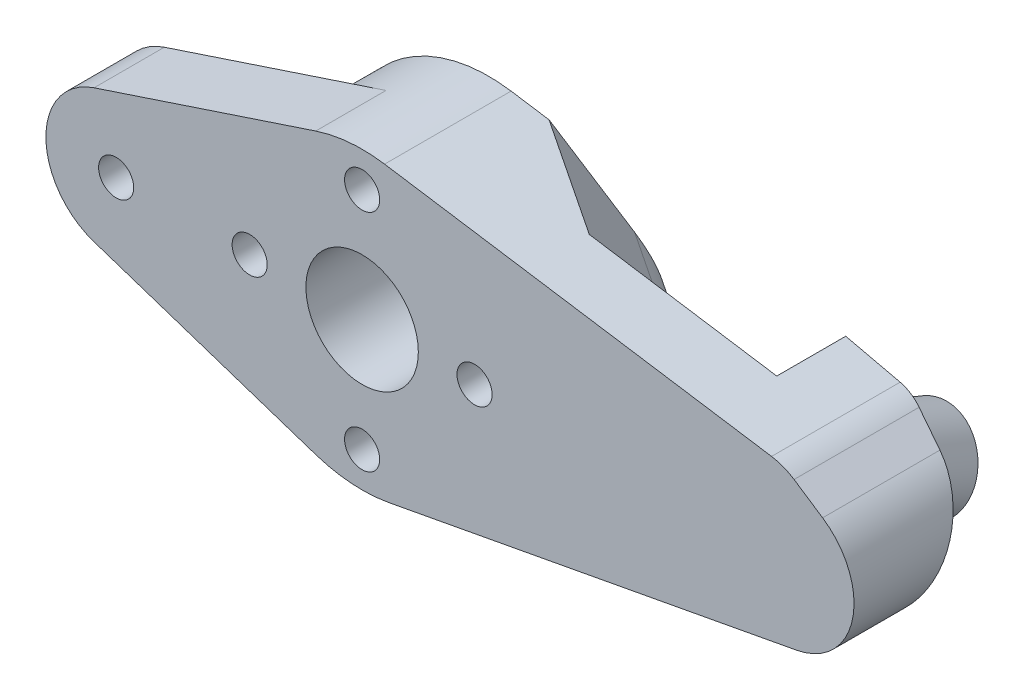
SolidWorks part; units mm, degrees
ref_plane "Plan de face" through (0, 0, 0) normal (0, 0, 1) x (1, 0, 0)
ref_plane "Plan de dessus" through (0, 0, 0) normal (0, 1, 0) x (1, 0, 0)
ref_plane "Plan de droite" through (0, 0, 0) normal (1, 0, 0) x (0, 0, -1)
sketch "Esquisse1" plane through (0, 0, 0) normal (0, 0, 1) x (1, 0, 0)
  line L1 (30.9167, -4.9153) -> (1.925, -10.322)
  line L2 (1.5995, 10.3775) -> (30, 6)
  line L3 (30, 6) -> (32.7639, 4.1667)
  arc A0 (1.5995, 10.3775) -> (1.925, -10.322) centre (0, 0) ccw
  arc A1 (32.7639, 4.1667) -> (30.9167, -4.9153) centre (30, 0) cw
  dimension "D1" = 10.5
  dimension "D2" = 5
  dimension "D3" = 30
  dimension "D4" = 6
extrude "Boss.-Extru.1" add sketch "Esquisse1" along normal blind 10
sketch "Esquisse2" plane through (0, 0, 10) normal (0, 0, 1) x (1, 0, 0)
  circle A0 centre (0, 0) radius 4
  circle A1 centre (0, 8) radius 1.25
  circle A2 centre (8, 0) radius 1.25
  circle A3 centre (0, -8) radius 1.25
  circle A4 centre (-8, 0) radius 1.25
  point P14 (0, 0)
  dimension "D1" = 2.5
  dimension "D2" = 8
  dimension "D3" = 8
  dimension "D4" = 4
extrude "Enlèv. mat.-Extru.1" cut sketch "Esquisse2" against normal up to next
sketch "Esquisse4" plane through (0, 0, 0) normal (0, 1, 0) x (1, 0, 0)
  line L0 (20, -5.5) -> (25, -5.5)
  line L1 (25, -5.5) -> (25, 0)
  line L2 (25, 0) -> (11, 0)
  line L3 (11, 0) -> (20, -5.5)
  line L5 (1.925, 0) -> (30.9167, 0) construction
  dimension "D1" = 11
  dimension "D2" = 9
  dimension "D3" = 5
  dimension "D4" = 5.5
extrude "Enlèv. mat.-Extru.2" cut sketch "Esquisse4" against normal up to next and the other way up to next
sketch "Esquisse5" plane through (0, 0, 0) normal (0, 0, -1) x (-1, 0, 0)
  line L3 (-25, -6.0187) -> (-25, 6.7707)
  line L4 (-25, 6.7707) -> (-30, 6)
  line L5 (-30.9167, -4.9153) -> (-25, -6.0187)
  line L6 (-25, -6.0187) -> (-25, 6.7707)
  line L8 (-30.9167, -4.9153) -> (-25, -6.0187)
  line L10 (-25, 6.7707) -> (-30, 6)
  line L11 (-30, 6) -> (-32.7639, 4.1667)
  line L12 (-30, 6) -> (-32.7639, 4.1667)
  arc A1 (-32.7639, 4.1667) -> (-30.9167, -4.9153) centre (-30, 0) ccw
  arc A2 (-32.7639, 4.1667) -> (-30.9167, -4.9153) centre (-30, 0) ccw
  dimension "D1" = 0
extrude "Boss.-Extru.2" add sketch "Esquisse5" along normal blind 2
sketch "Esquisse6" plane through (25, 0, 0) normal (-1, 0, 0) x (0, 0, 1)
  line L0 (-2, 6.7707) -> (3.214, -6.0187)
  line L1 (-2, -6.0187) -> (5.5, -6.0187) construction
  line L2 (3.214, -6.0187) -> (-2, -6.0187)
  line L3 (-2, -6.0187) -> (-2, 6.7707)
  line L4 (-2, -6.0187) -> (-2, 6.7707) construction
  dimension "D1" = 22.18
extrude "Enlèv. mat.-Extru.3" cut sketch "Esquisse6" against normal up to next
sketch "Esquisse7" plane through (0, 0.2658, 0.6519) normal (0, -0.3775, -0.926) x (-1, 0, 0)
  line L0 (8, 0) -> (-34.9929, 0) construction
  line L1 (-25, -6.7867) -> (-25, 7.0247) construction
  circle A0 centre (-30, 1.25) radius 1.25
  ellipse E0 centre (8, 0) end of major axis (9.25, 0) minor radius 1.1575 construction
  ellipse E1 centre (-8, 0) end of major axis (-6.75, 0) minor radius 1.1575 construction
  ellipse E2 centre (8, 0) end of major axis (9.25, 0) minor radius 1.1575 construction
  ellipse E3 centre (-8, 0) end of major axis (-6.75, 0) minor radius 1.1575 construction
  ellipse E4 centre (-30, -0.287) end of major axis (-30, 5.1125) minor radius 5 (-32.7639, 4.2126) -> (-30.9167, -5.5951) ccw construction
  dimension "D2" = 2.5
  dimension "D1" = 5
  dimension "D3" = 1.25
extrude "Enlèv. mat.-Extru.4" cut sketch "Esquisse7" against normal blind 6
sketch "Esquisse8" plane through (0, 0.2658, 0.6519) normal (0, -0.3775, -0.926) x (-1, 0, 0)
  line L0 (-25, -10.8272) -> (-25, 10.9138)
  line L1 (-25, 10.9138) -> (-38.8482, 10.9138)
  line L2 (-38.8482, 10.9138) -> (-38.8482, -10.8272)
  line L3 (-38.8482, -10.8272) -> (-25, -10.8272)
  line L4 (-25, -6.7867) -> (-25, 7.0247) construction
extrude "Enlèv. mat.-Extru.5" cut sketch "Esquisse8" against normal blind 2.4
sketch "Esquisse9" plane through (0, 1.1718, 2.8743) normal (0, -0.3775, -0.926) x (-1, 0, 0)
  line L1 (-30, 5.214) -> (-32.7639, 3.2342) construction
  circle A0 centre (-30, 1.25) radius 3.2225
  circle A1 centre (-30, 1.25) radius 1.25 construction
  circle A2 centre (-30, 1.25) radius 1.25
extrude "Boss.-Extru.3" add sketch "Esquisse9" along normal blind 3
chamfer "Chanfrein1" distance 4 angle 45 2 edges at (15.5, -7.7904, 2.75) (15.5, 8.2349, 2.75)
fillet "Congé1" radius 4 3 edges at (15.5, -3.2891, 2.75) (30, 6, 5.453) (15.5, 4.2005, 2.75)
sketch "Esquisse10" plane through (0, 0, 0) normal (0, 0, -1) x (-1, 0, 0)
  circle A4 centre (0, 0) radius 15.6017
extrude "Enlèv. mat.-Extru.6" cut sketch "Esquisse10" against normal blind 1
sketch "Esquisse13" plane through (0, 0, 10) normal (0, 0, 1) x (1, 0, 0)
  line L0 (-3.3, -9.9679) -> (-19.0714, -4.7466)
  line L1 (0, 0) -> (-17.5, 0) construction
  line L2 (-19.0714, 4.7466) -> (-3.3, 9.9679)
  arc A0 (1.5995, 10.3775) -> (1.925, -10.322) centre (0, 0) ccw construction
  arc A1 (-19.0714, -4.7466) -> (-19.0714, 4.7466) centre (-17.5, 0) cw
  arc A2 (-3.3, -9.9679) -> (-3.3, 9.9679) centre (0, 0) cw
  circle A3 centre (-17.5, 0) radius 1.25
  dimension "D2" = 2.5
  dimension "D3" = 5
  dimension "D1" = 17.5
extrude "Boss.-Extru.5" add sketch "Esquisse13" against normal blind 5
sketch "Esquisse14" plane through (-3.3, -9.9679, 0) normal (-0.3143, -0.9493, 0) x (0.9493, -0.3143, 0)
  line L0 (-16.6132, 5) -> (-16.6132, 10) construction
  line L1 (-16.6132, 5) -> (0, 5) construction
  text T0 "<b>M3</b>"
  dimension "D1" = 1
  dimension "D2" = 0.75
extrude "Enlèv. mat.-Extru.7" cut sketch "Esquisse14" against normal blind 1.5
